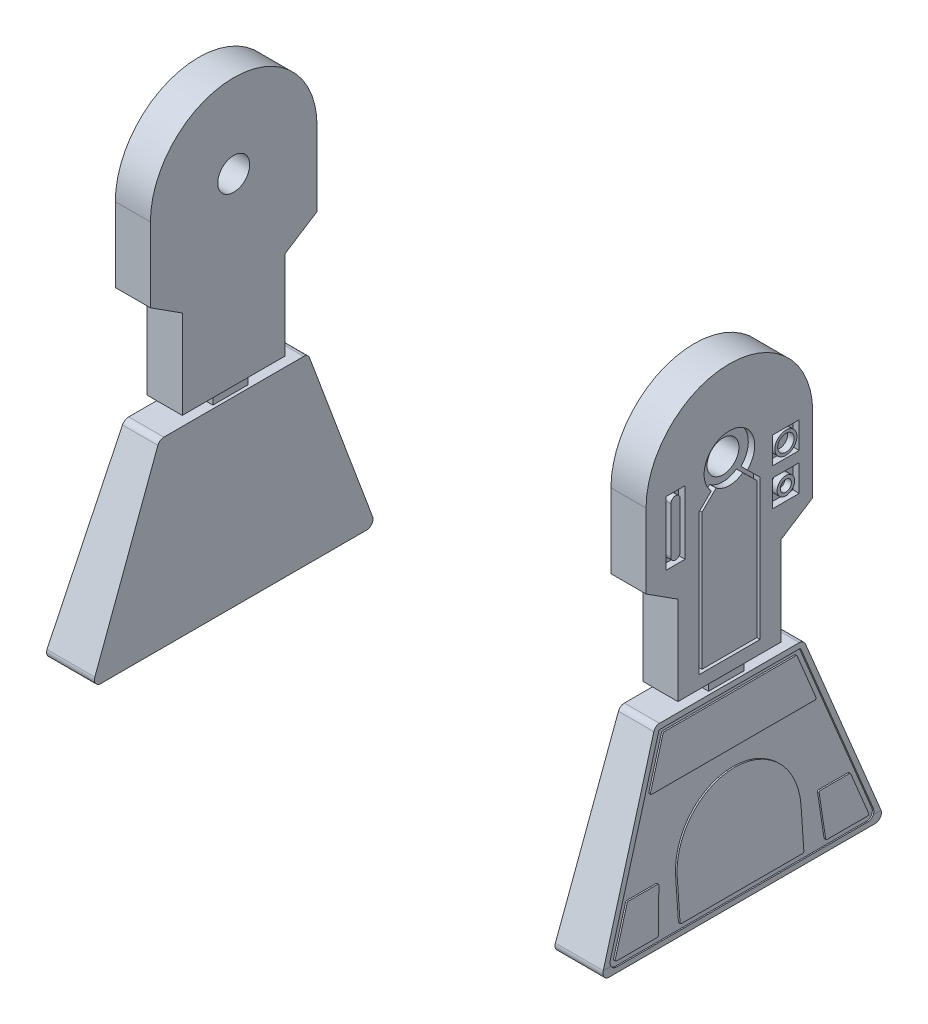
SolidWorks part; units mm, degrees
ref_plane "Front Plane" through (0, 0, 0) normal (0, 0, 1) x (1, 0, 0)
ref_plane "Top Plane" through (0, 0, 0) normal (0, 1, 0) x (1, 0, 0)
ref_plane "Right Plane" through (0, 0, 0) normal (1, 0, 0) x (0, 0, -1)
ref_plane "Plane4" through (172.1009, 9.1621, -1.5034) normal (1, 0, 0) x (0, 0, -1)
sketch "Sketch1" plane through (172.1009, 0, 0) normal (1, 0, 0) x (0, 0, -1)
  line L0 (-91.8367, 139.4871) -> (-119.6361, 139.4871)
  line L1 (-122.0162, 137.8342) -> (-147.1029, 70.5242)
  line L2 (-144.7228, 67.0971) -> (-38.9507, 67.0971)
  line L3 (-36.5706, 70.5242) -> (-61.6573, 137.8342)
  line L4 (-64.0373, 139.4871) -> (-91.8367, 139.4871)
  circle A0 centre (-91.8367, 100.1171) radius 35 construction
  arc A1 (-38.9507, 67.0971) -> (-36.5706, 70.5242) centre (-38.9507, 69.6371) ccw
  arc A2 (-147.1029, 70.5242) -> (-144.7228, 67.0971) centre (-144.7228, 69.6371) ccw
  arc A3 (-61.6573, 137.8342) -> (-64.0373, 139.4871) centre (-64.0373, 136.9471) ccw
  arc A4 (-119.6361, 139.4871) -> (-122.0162, 137.8342) centre (-119.6361, 136.9471) ccw
  point P5 (-121.2136, 129.1394)
  point P6 (-63.0489, 128.5127)
  point P7 (0, 0)
  point P9 (0, 0)
  point P10 (-151.5703, 57.4426)
  point P11 (-91.8367, 67.0971)
  point P12 (0, 0)
  dimension "D3" = 2.54
  dimension "D1" = 39.37
  dimension "D2" = 33.02
extrude "Boss-Extrude1" add sketch "Sketch1" along normal blind 19.05
sketch "Sketch21" plane through (0, 29.0214, -1.5034) normal (0, 0, 1) x (1, 0, 0)
  line L1 (191.1509, 108.8128) -> (191.1509, 110.4657) construction
  line L2 (172.1009, 110.4657) -> (191.1509, 110.4657) construction
  line L3 (191.1509, 108.8128) -> (191.1509, 41.5028) construction
  line L5 (191.1509, 108.8128) -> (191.1509, 110.4657)
  line L6 (186.0709, 110.4657) -> (191.1509, 110.4657)
  line L7 (191.1509, 108.8128) -> (191.1509, 41.5028)
  line L8 (191.1509, 41.5028) -> (186.0709, 110.4657)
  point P0 (0, 0)
  point P7 (0, 0)
  dimension "D1" = 5.08
extrude "Cut-Extrude9" cut sketch "Sketch21" against normal through all both and the other way through all
sketch "Sketch3" plane through (196.2976, 0.6558, 0) normal (0.9973, 0.0735, 0) x (0, 0, -1)
  line L10 (-141.6084, 68.6719) -> (-41.8772, 68.6719)
  line L13 (-64.0373, 137.1755) -> (-119.6361, 137.1755)
  line L14 (-120.1115, 136.8421) -> (-144.1797, 72.0897)
  line L15 (-144.1797, 72.0897) -> (-39.4937, 72.0897)
  line L16 (-39.4937, 72.0897) -> (-63.562, 136.8421)
  line L17 (-64.0373, 137.1755) -> (-119.6361, 137.1755)
  line L18 (-120.1115, 136.8421) -> (-144.1797, 72.0897)
  line L20 (-39.4937, 72.0897) -> (-63.562, 136.8421)
  line L21 (-144.7228, 66.6399) -> (-38.9507, 66.6399) construction
  arc A10 (-41.8772, 68.6719) -> (-39.4937, 72.0897) centre (-41.8772, 71.2119) ccw
  arc A11 (-144.1797, 72.0897) -> (-141.6084, 68.6719) centre (-141.7989, 71.2047) ccw
  spline S0 degree 3 poles (-1871.195, -826.1196) (-67.5077, 74.6539) (-115.6572, 140.0845) (-124.1043, 134.1459) (-81.9384, 67.9061) (1273.7511, 1569.8087) knots -24.827017 -24.827017 -24.827017 -24.827017 0.5 0.5 25.294933 25.294933 25.294933 25.294933 only from (-119.6361, 137.1755) to (-120.1115, 136.8421)
  spline S1 degree 3 poles (-119.6361, 137.1755) (-119.74, 137.1755) (-119.8414, 137.1429) (-120.0099, 137.0244) (-120.0753, 136.9394) (-120.1115, 136.8421) knots 0 0 0 0 0.5 0.5 1 1 1 1
  spline S2 degree 3 poles (-1481.974, 1545.4362) (-105.2214, 65.4309) (-59.4487, 134.0493) (-67.8114, 139.9518) (-114.8013, 81.4005) (1697.0132, -809.096) knots -25.079329 -25.079329 -25.079329 -25.079329 0.5 0.5 24.686986 24.686986 24.686986 24.686986 only from (-63.562, 136.8421) to (-64.0373, 137.1755)
  spline S3 degree 3 poles (-63.562, 136.8421) (-63.5981, 136.9395) (-63.663, 137.0238) (-63.8311, 137.1424) (-63.9334, 137.1755) (-64.0373, 137.1755) knots 0 0 0 0 0.5 0.5 1 1 1 1
  dimension "D2" = 2.032
  dimension "D1" = 2.032
extrude "Cut-Extrude2" cut sketch "Sketch3" against normal blind 0.635
sketch "Sketch4" plane through (195.6626, 0.6324, 0) normal (0.9973, 0.0735, 0) x (0, 0, -1)
  line L0 (-118.0364, 135.6191) -> (-65.637, 135.6191)
  line L1 (-65.1609, 135.2881) -> (-58.9058, 118.4596)
  line L2 (-59.3819, 117.7746) -> (-124.2915, 117.7746)
  line L4 (-124.7677, 118.4596) -> (-118.5126, 135.2881)
  line L7 (-140.5891, 70.6734) -> (-125.6435, 70.6734)
  line L8 (-125.1375, 71.1368) -> (-123.7232, 87.178)
  line L9 (-124.2293, 87.7307) -> (-135.8364, 87.7307)
  line L10 (-136.3126, 87.3996) -> (-142.2751, 71.3584)
  line L11 (-141.7989, 70.6734) -> (-140.5891, 70.6734)
  line L12 (-91.8367, 67.0971) -> (-91.8367, 138.8109) construction
  line L14 (-61.6573, 137.5267) -> (-36.5706, 70.0343) construction
  line L15 (-64.0373, 138.8109) -> (-119.6361, 138.8109) construction
  line L16 (-41.8746, 70.6734) -> (-43.0843, 70.6734)
  line L17 (-47.3609, 87.3996) -> (-41.3984, 71.3584)
  line L18 (-59.4442, 87.7307) -> (-47.837, 87.7307)
  line L19 (-58.536, 71.1368) -> (-59.9502, 87.178)
  line L20 (-43.0843, 70.6734) -> (-58.0299, 70.6734)
  line L22 (-116.4717, 71.1814) -> (-116.4717, 86.4452)
  line L23 (-67.2017, 86.4452) -> (-67.2017, 71.1814)
  line L25 (-67.7097, 70.6734) -> (-115.9637, 70.6734)
  line L26 (-147.1029, 70.0343) -> (-122.0162, 137.5267) construction
  arc A0 (-144.0651, 70.0343) -> (-141.6084, 68.6485) centre (-141.7989, 71.1814) ccw construction
  arc A2 (-58.9058, 118.4596) -> (-59.3819, 117.7746) centre (-59.3819, 118.2826) cw
  arc A3 (-65.637, 135.6191) -> (-65.1609, 135.2881) centre (-65.637, 135.1111) cw
  arc A4 (-124.2915, 117.7746) -> (-124.7677, 118.4596) centre (-124.2915, 118.2826) cw
  arc A5 (-118.0364, 135.6191) -> (-118.5126, 135.2881) centre (-118.0364, 135.1111) ccw
  arc A6 (-116.4717, 86.4452) -> (-67.2017, 86.4452) centre (-91.8367, 86.4452) cw
  arc A7 (-116.4717, 71.1814) -> (-115.9637, 70.6734) centre (-115.9637, 71.1814) ccw
  arc A8 (-67.2017, 71.1814) -> (-67.7097, 70.6734) centre (-67.7097, 71.1814) cw
  arc A9 (-58.536, 71.1368) -> (-58.0299, 70.6734) centre (-58.0299, 71.1814) ccw
  arc A10 (-41.8746, 70.6734) -> (-41.3984, 71.3584) centre (-41.8746, 71.1814) ccw
  arc A11 (-47.3609, 87.3996) -> (-47.837, 87.7307) centre (-47.837, 87.2227) ccw
  arc A12 (-59.4442, 87.7307) -> (-59.9502, 87.178) centre (-59.4442, 87.2227) ccw
  arc A13 (-142.2751, 71.3584) -> (-141.7989, 70.6734) centre (-141.7989, 71.1814) ccw
  arc A14 (-125.6435, 70.6734) -> (-125.1375, 71.1368) centre (-125.6435, 71.1814) ccw
  arc A15 (-123.7232, 87.178) -> (-124.2293, 87.7307) centre (-124.2293, 87.2227) ccw
  arc A16 (-135.8364, 87.7307) -> (-136.3126, 87.3996) centre (-135.8364, 87.2227) ccw
  point P2 (0, 0)
  point P13 (0, 0)
  point P19 (-65.2839, 135.6191)
  point P24 (-118.3896, 135.6191)
  point P37 (-141.4752, 69.6704)
  point P50 (0, 0)
  point P56 (-116.4717, 70.6734)
  point P59 (-67.2017, 70.6734)
  point P62 (-58.4951, 70.6734)
  point P65 (-41.1438, 70.6734)
  point P68 (-47.4839, 87.7307)
  point P71 (-59.9989, 87.7307)
  point P74 (-142.5297, 70.6734)
  point P77 (-125.1783, 70.6734)
  point P80 (-123.6745, 87.7307)
  point P83 (-136.1895, 87.7307)
  dimension "D1" = 0.508
  dimension "D2" = 0.508
extrude "Boss-Extrude2" add sketch "Sketch4" along normal blind 0.635
sketch "Sketch5" plane through (0, 139.4871, 0) normal (0, 1, 0) x (1, 0, 0)
  line L0 (173.3709, -98.8367) -> (173.3709, -84.8367)
  line L1 (173.3709, -84.8367) -> (184.8009, -84.8367)
  line L3 (184.8009, -84.8367) -> (184.8009, -98.8367)
  line L5 (173.3709, -98.8367) -> (184.8009, -98.8367)
  line L7 (172.1009, -64.0373) -> (186.0709, -64.0373) construction
  line L10 (172.1009, -64.0373) -> (172.1009, -119.6361) construction
  line L11 (144.906, -98.8367) -> (142.906, -98.8367) construction
  line L12 (142.906, -84.8367) -> (144.906, -84.8367) construction
  point P4 (169.5609, -85.0987)
  point P5 (173.3709, -85.1365)
  point P8 (169.5609, -97.9449)
  point P9 (0, 0)
  point P12 (179.0859, -64.0373)
  point P13 (179.0859, -84.8367)
  point P14 (172.1009, -91.8367)
  point P15 (173.3709, -91.8367)
  dimension "D1" = 1.27
extrude "Cut-Extrude3" cut sketch "Sketch5" against normal blind 1.27
sketch "Sketch6" plane through (0, 138.2171, 0) normal (0, 1, 0) x (1, 0, 0)
  line L8 (173.3709, -98.8367) -> (184.8009, -98.8367)
  line L9 (184.8009, -98.8367) -> (184.8009, -84.8367)
  line L11 (184.8009, -84.8367) -> (173.3709, -84.8367)
  line L16 (173.3709, -84.8367) -> (173.3709, -98.8367)
  line L18 (173.3709, -98.8367) -> (184.8009, -98.8367)
  line L19 (184.8009, -98.8367) -> (184.8009, -84.8367)
  line L20 (184.8009, -84.8367) -> (173.3709, -84.8367)
  line L21 (173.3709, -84.8367) -> (173.3709, -98.8367)
  dimension "D1" = 0
extrude "Boss-Extrude3" add sketch "Sketch6" along normal blind 5.08
sketch "Sketch10" plane through (191.1509, 0, 0) normal (1, 0, 0) x (0, 0, -1)
  line L0 (-112.3078, 143.2971) -> (-112.3078, 178.595)
  line L1 (-112.3078, 178.595) -> (-124.9926, 186.7263)
  line L2 (-91.8367, 139.4871) -> (-91.8367, 203.1511) construction
  line L3 (-64.0373, 139.4871) -> (-119.6361, 139.4871) construction
  line L4 (-124.9926, 186.7263) -> (-124.9926, 216.3242)
  line L5 (-58.6808, 186.7263) -> (-58.6808, 216.3242)
  line L6 (-71.3656, 178.595) -> (-58.6808, 186.7263)
  line L7 (-71.3656, 143.2971) -> (-71.3656, 178.595)
  line L8 (-71.3656, 143.2971) -> (-112.3078, 143.2971)
  line L9 (-98.8367, 143.2971) -> (-84.8367, 143.2971) construction
  arc A0 (-124.9926, 216.3242) -> (-58.6808, 216.3242) centre (-91.8367, 216.3242) cw
  point P12 (0, 0)
  point P16 (-91.8367, 203.1511)
  point P17 (-121.2985, 203.1511)
  point P18 (-119.5464, 179.4316)
  point P19 (-107.9673, 196.3963)
  point P20 (-125.4706, 217.4002)
  point P21 (-127.6248, 242.1741)
  point P22 (-124.3935, 210.6682)
  point P23 (-125.2013, 233.8263)
  point P24 (-121.1621, 207.7061)
  point P25 (-121.0432, 223.8281)
  point P26 (-117.8848, 205.5098)
  point P27 (-107.1466, 187.1916)
  point P28 (-117.569, 193.5082)
  point P29 (-125.3179, 216.3242)
  point P30 (-125.3179, 189.3283)
  point P31 (-112.3078, 178.595)
  point P32 (-124.9926, 186.7263)
extrude "Boss-Extrude5" add sketch "Sketch10" against normal up to surface (13.97 mm away) from vertex at -5.08 up to face at (172.1009, 103.6732, 91.8367)
sketch "Sketch11" plane through (186.0709, 0, 0) normal (1, 0, 0) x (0, 0, -1)
  line L0 (-79.6625, 148.3771) -> (-104.011, 148.3771)
  line L1 (-104.011, 148.3771) -> (-104.011, 204.3343)
  line L2 (-104.011, 204.3343) -> (-99.0104, 209.2591)
  line L3 (-91.8367, 258.0721) -> (-91.8367, 135.9318) construction
  line L4 (-65.637, 135.9318) -> (-118.0364, 135.9318) construction
  line L5 (-79.6625, 204.3343) -> (-84.663, 209.2591)
  line L6 (-79.6625, 148.3771) -> (-79.6625, 204.3343)
  line L7 (-112.3078, 143.2971) -> (-71.3656, 143.2971) construction
  line L9 (-117.094, 216.3242) -> (-109.474, 216.3242)
  line L10 (-117.094, 216.3242) -> (-117.094, 190.9242)
  line L11 (-117.094, 190.9242) -> (-109.474, 190.9242)
  line L12 (-109.474, 216.3242) -> (-109.474, 190.9242)
  line L13 (-74.6633, 216.3242) -> (-64.0545, 216.3242)
  line L14 (-74.6633, 216.3242) -> (-74.6633, 205.7153)
  line L15 (-74.6633, 205.7153) -> (-64.0545, 205.7153)
  line L16 (-64.0545, 216.3242) -> (-64.0545, 205.7153)
  line L17 (-74.6633, 201.533) -> (-64.0545, 201.533)
  line L18 (-74.6633, 201.533) -> (-74.6633, 190.9242)
  line L19 (-74.6633, 190.9242) -> (-64.0545, 190.9242)
  line L20 (-64.0545, 201.533) -> (-64.0545, 190.9242)
  arc A0 (-84.663, 209.2591) -> (-99.0104, 209.2591) centre (-91.8367, 216.3242) ccw
  arc A2 (-58.6808, 216.3242) -> (-124.9926, 216.3242) centre (-91.8367, 216.3242) ccw construction
  point P16 (-91.8367, 148.3771)
  point P29 (-112.4546, 233.9284)
  point P30 (-76.3146, 223.6394)
  point P31 (-66.2829, 223.5108)
  point P32 (-66.2829, 218.6235)
  point P33 (-76.3146, 219.781)
  point P34 (-100.2303, 216.6044)
  point P35 (0, 0)
  point P36 (-65.5919, 216.3242)
  point P37 (-65.8994, 216.3242)
  point P38 (-102.329, 215.858)
  point P39 (-109.7526, 198.6797)
  point P40 (-64.0545, 205.7153)
  dimension "D1" = 5.08
  dimension "D5" = 7.62
extrude "Cut-Extrude4" cut sketch "Sketch11" against normal blind 2.54
sketch "Sketch12" plane through (183.5309, 0, 0) normal (1, 0, 0) x (0, 0, -1)
  line L0 (-109.474, 190.9242) -> (-109.474, 216.3242) construction
  line L1 (-109.474, 216.3242) -> (-117.094, 216.3242) construction
  line L2 (-64.0545, 216.3242) -> (-74.6633, 216.3242) construction
  line L3 (-74.6633, 216.3242) -> (-74.6633, 205.7153) construction
  line L4 (-74.6633, 201.533) -> (-74.6633, 190.9242) construction
  line L5 (-64.0545, 201.533) -> (-74.6633, 201.533) construction
  line L17 (-113.284, 212.8697) -> (-113.284, 194.3786) construction
  line L18 (-111.4527, 212.8697) -> (-111.4527, 194.3786)
  line L19 (-115.1153, 212.8697) -> (-115.1153, 194.3786)
  line L22 (-102.741, 203.8026) -> (-102.741, 149.6471)
  line L23 (-102.741, 149.6471) -> (-80.9325, 149.6471)
  line L24 (-80.9325, 149.6471) -> (-80.9325, 203.8026)
  line L25 (-80.9325, 203.8026) -> (-86.5246, 209.3101)
  line L26 (-97.1488, 209.3101) -> (-102.741, 203.8026)
  line L27 (-102.741, 203.8026) -> (-102.741, 149.6471)
  line L28 (-102.741, 149.6471) -> (-80.9325, 149.6471)
  line L29 (-80.9325, 149.6471) -> (-80.9325, 203.8026)
  line L30 (-80.9325, 203.8026) -> (-86.5246, 209.3101)
  line L31 (-97.1488, 209.3101) -> (-102.741, 203.8026)
  arc A2 (-97.1488, 209.3101) -> (-86.5246, 209.3101) centre (-91.8367, 216.3242) ccw
  arc A3 (-86.5246, 209.3101) -> (-97.1488, 209.3101) centre (-91.8367, 216.3242) ccw
  circle A5 centre (-91.8367, 216.3242) radius 6.35
  circle A6 centre (-69.3589, 211.0197) radius 4.3774
  circle A7 centre (-69.3589, 211.0197) radius 3.2637
  circle A8 centre (-69.3589, 196.2286) radius 3.4952
  circle A9 centre (-69.3589, 196.2286) radius 2.209
  arc A10 (-111.4527, 212.8697) -> (-115.1153, 212.8697) centre (-113.284, 212.8697) ccw
  arc A11 (-115.1153, 194.3786) -> (-111.4527, 194.3786) centre (-113.284, 194.3786) ccw
  point P11 (-113.284, 203.6242)
  point P16 (-98.6116, 224.3751)
  point P18 (-100.7837, 223.9275)
  point P20 (0, 0)
  point P23 (-109.474, 203.6242)
  point P26 (-113.284, 216.3242)
  point P27 (0, 0)
  point P30 (-69.3589, 216.3242)
  point P33 (-74.6633, 211.0197)
  point P35 (0, 0)
  point P40 (-74.6633, 196.2286)
  point P45 (-69.3589, 201.533)
  point P46 (-113.284, 203.8026)
  point P47 (-115.1153, 194.3786)
  dimension "D2" = 12.7
  dimension "D1" = 1.27
extrude "Boss-Extrude6" add sketch "Sketch12" along normal blind 2.54
ref_plane "Mid plane" through (80.466, 0, 0) normal (1, 0, 0) x (0, 0, -1)
sketch "Sketch18" plane through (0, 0, 0) normal (0, 0, 1) x (1, 0, 0)
  line L0 (172.1009, 137.8342) -> (172.1009, 70.5242) construction
  line L1 (172.1009, 90.7521) -> (152.8516, 90.7521)
  line L2 (172.1009, 90.7521) -> (172.1009, 79.9821)
  line L3 (172.1009, 79.9821) -> (152.8516, 79.9821)
  line L4 (152.8516, 90.7521) -> (152.8516, 79.9821)
  line L5 (152.8516, 80.6171) -> (152.8516, 90.1171) construction
  line L6 (152.3053, 90.1171) -> (144.1861, 90.1171) construction
  line L7 (146.0764, 80.6171) -> (147.1005, 80.6171) construction
  dimension "D1" = 0.635
  dimension "D2" = 0.635
extrude "Cut-Extrude7" [suppressed] cut sketch "Sketch18" against normal through all both and the other way through all
mirror "Mirror4" about plane through (80.466, 0, 0) normal (1, 0, 0) of bodies 110
sketch "Sketch23" plane through (186.0709, 0, 0) normal (1, 0, 0) x (0, 0, -1)
  circle A1 centre (-91.8367, 216.3242) radius 6.35
  circle A2 centre (-91.8367, 216.3242) radius 6.35
  dimension "D1" = 0
extrude "Cut-Extrude10" cut sketch "Sketch23" against normal through all both and the other way through all
ref_plane "Base plane" [suppressed] through (0, 71.455, 0) normal (0, -1, 0) x (-1, 0, 0)
sketch "Sketch13" [suppressed] plane through (0, 71.455, 0) normal (0, -1, 0) x (-1, 0, 0)
  line L3 (-36.3851, -36.6066) -> (-36.3851, -64.7) construction
  line L4 (-38.9651, -151.6617) -> (-38.9651, -35.0313)
  line L5 (-163.8451, -35.0647) -> (-163.8451, -151.6283)
  line L14 (-166.4251, -148.7346) -> (-166.4251, -156.6463)
  line L15 (-166.4251, -156.6463) -> (-178.3631, -156.6463)
  line L16 (-178.3631, -156.6463) -> (-178.3631, -30.0467)
  line L17 (-178.3631, -30.0467) -> (-166.4251, -30.0467)
  line L19 (-166.4251, -30.0467) -> (-166.4251, -37.9584)
  line L20 (-36.3851, -37.9218) -> (-36.3851, -30.0101)
  line L21 (-36.3851, -30.0101) -> (-24.4471, -30.0101)
  line L22 (-24.4471, -30.0101) -> (-24.4471, -156.6829)
  line L23 (-24.4471, -156.6829) -> (-36.3851, -156.6829)
  line L24 (-36.3851, -156.6829) -> (-36.3851, -148.7712)
  arc A4 (-38.9651, -35.0313) -> (-163.8451, -35.0647) centre (-101.3896, -93.3465) ccw
  arc A5 (-163.8451, -151.6283) -> (-38.9651, -151.6617) centre (-101.3896, -93.3465) ccw
  arc A6 (-36.3851, -37.9218) -> (-166.4251, -37.9584) centre (-101.3896, -93.3465) ccw
  arc A7 (-166.4251, -148.7346) -> (-36.3851, -148.7712) centre (-101.3896, -93.3465) ccw
  point P2 (0, 0)
  dimension "D1" = 0
extrude "Boss-Extrude7" [suppressed] add sketch "Sketch13" along normal up to surface and the other way up to vertex
sketch "Sketch17" [suppressed] plane through (0, 190.684, 0) normal (0, 1, 0) x (1, 0, 0)
  line L20 (34.0991, -32.2961) -> (26.7331, -32.2961)
  line L21 (26.7331, -32.2961) -> (26.7331, -154.3969)
  line L22 (26.7331, -154.3969) -> (34.0991, -154.3969)
  line L23 (34.0991, -154.3969) -> (34.0991, -142.1741)
  line L24 (168.7111, -142.1311) -> (168.7111, -154.3603)
  line L25 (168.7111, -154.3603) -> (176.0771, -154.3603)
  line L26 (176.0771, -154.3603) -> (176.0771, -32.3327)
  line L27 (176.0771, -32.3327) -> (168.7111, -32.3327)
  line L28 (168.7111, -32.3327) -> (168.7111, -44.5619)
  line L29 (34.0991, -44.5189) -> (34.0991, -32.2961)
  line L30 (34.0991, -32.2961) -> (26.7331, -32.2961)
  line L31 (26.7331, -32.2961) -> (26.7331, -154.3969)
  line L32 (26.7331, -154.3969) -> (34.0991, -154.3969)
  line L33 (34.0991, -154.3969) -> (34.0991, -142.1741)
  line L34 (168.7111, -142.1311) -> (168.7111, -154.3603)
  line L35 (168.7111, -154.3603) -> (176.0771, -154.3603)
  line L36 (176.0771, -154.3603) -> (176.0771, -32.3327)
  line L37 (176.0771, -32.3327) -> (168.7111, -32.3327)
  line L38 (168.7111, -32.3327) -> (168.7111, -44.5619)
  line L39 (34.0991, -44.5189) -> (34.0991, -32.2961)
  arc A4 (34.0991, -142.1741) -> (168.7111, -142.1311) centre (101.3896, -93.3465) ccw
  arc A5 (168.7111, -44.5619) -> (34.0991, -44.5189) centre (101.3896, -93.3465) ccw
  arc A6 (34.0991, -142.1741) -> (168.7111, -142.1311) centre (101.3896, -93.3465) ccw
  arc A7 (168.7111, -44.5619) -> (34.0991, -44.5189) centre (101.3896, -93.3465) ccw
  dimension "D1" = 2.286
extrude "Cut-Extrude5" [suppressed] cut sketch "Sketch17" against normal through all both and the other way through all
